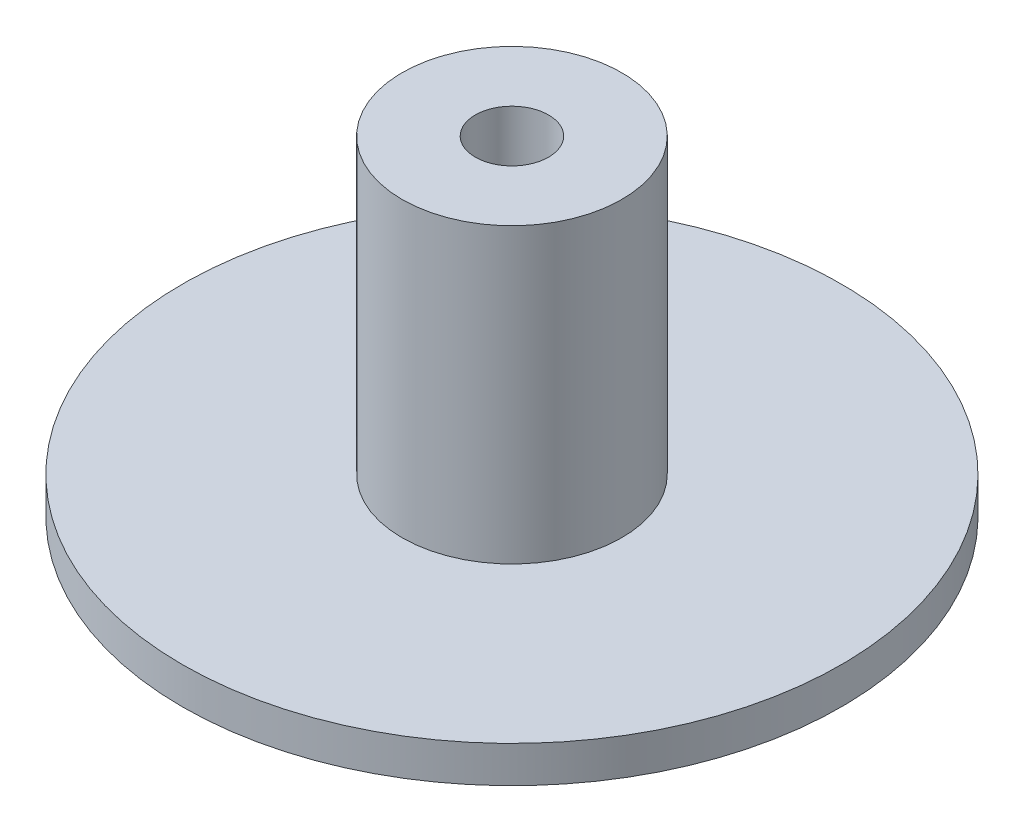
SolidWorks part; units mm, degrees
ref_plane "Front Plane" through (0, 0, 0) normal (0, 0, 1) x (1, 0, 0)
ref_plane "Top Plane" through (0, 0, 0) normal (0, 1, 0) x (1, 0, 0)
ref_plane "Right Plane" through (0, 0, 0) normal (1, 0, 0) x (0, 0, -1)
sketch "Sketch2" plane through (0, 0, 0) normal (0, 0, 1) x (1, 0, 0)
  line L0 (0, 0) -> (0, -6.35)
  line L1 (0, 0) -> (57.15, 0)
  line L2 (57.15, 0) -> (57.15, -6.35)
  line L3 (57.15, -6.35) -> (0, -6.35)
  dimension "D1" = 6.35
  dimension "D2" = 57.15
revolve "Revolve1" add sketch "Sketch2" angle 360 about L0
sketch "Sketch3" plane through (0, 0, 0) normal (0, 1, 0) x (1, 0, 0)
  circle A0 centre (0, 0) radius 19.05
extrude "Boss-Extrude1" add sketch "Sketch3" along normal blind 50.8
sketch "Sketch4" plane through (0, 50.8, 0) normal (0, 1, 0) x (1, 0, 0)
  circle A0 centre (0, 0) radius 6.35
extrude "Cut-Extrude1" cut sketch "Sketch4" against normal blind 81.026
